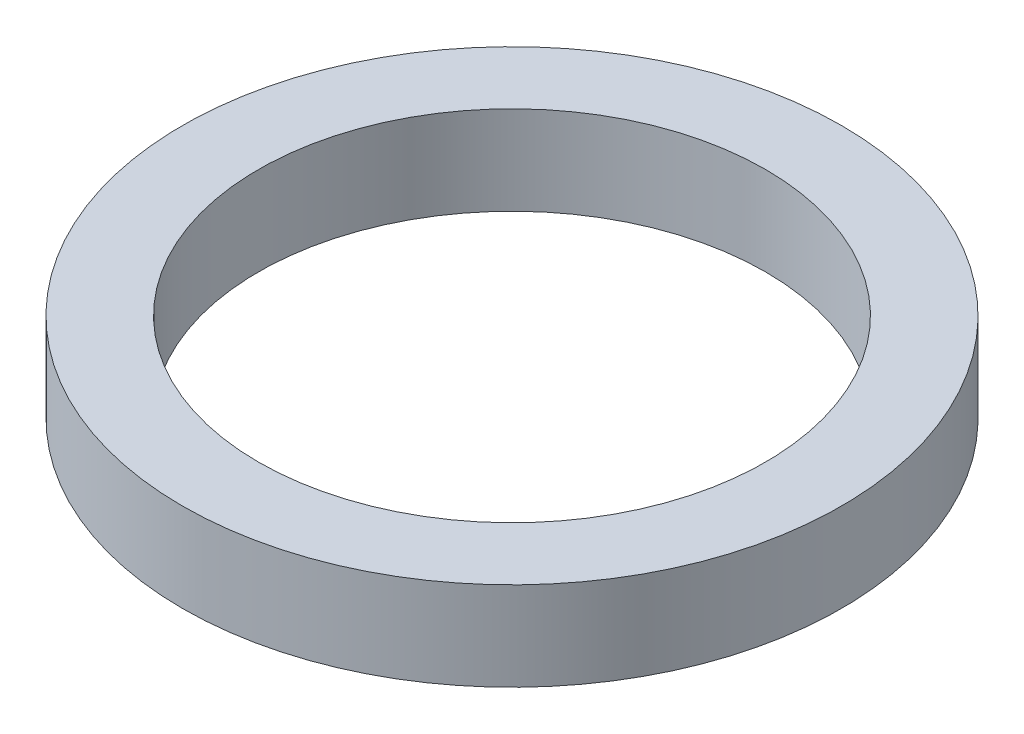
SolidWorks part; units mm, degrees
ref_plane "前视基准面" through (0, 0, 0) normal (0, 0, 1) x (1, 0, 0)
ref_plane "上视基准面" through (0, 0, 0) normal (0, 1, 0) x (1, 0, 0)
ref_plane "右视基准面" through (0, 0, 0) normal (1, 0, 0) x (0, 0, -1)
other "Configuration Table"
sketch "草图1" plane through (0, 0, 0) normal (0, 1, 0) x (1, 0, 0)
  circle A0 centre (0, 0) radius 20
  circle A1 centre (0, 0) radius 26
  dimension "D1" = 40
  dimension "D2" = 52
extrude "凸台-拉伸1" add sketch "草图1" along normal blind 7
